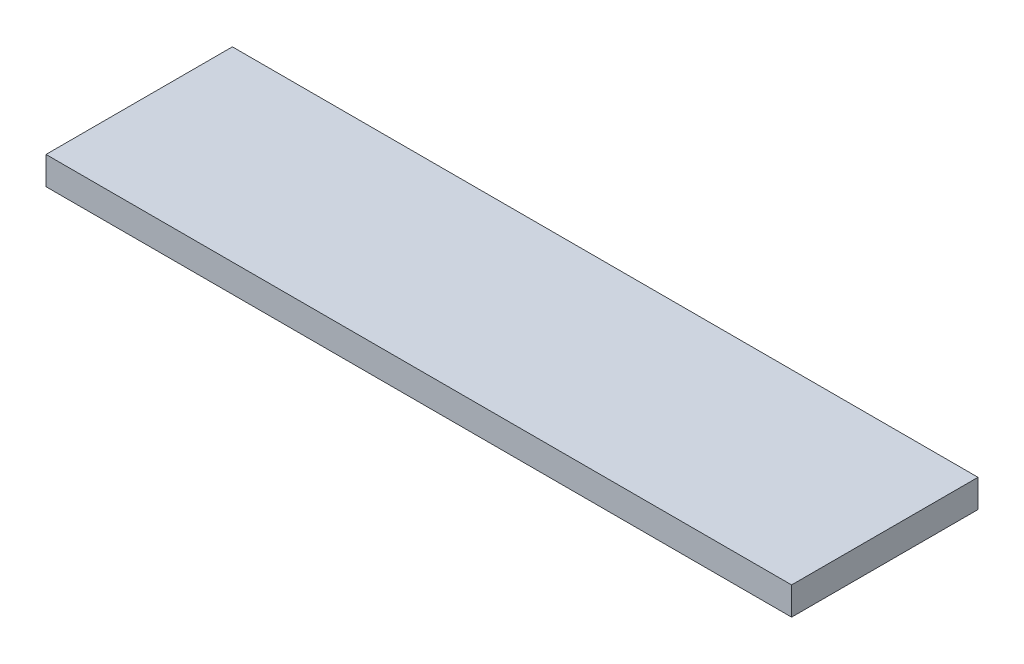
SolidWorks part; units mm, degrees
ref_plane "Front" through (0, 0, 0) normal (0, 0, 1) x (1, 0, 0)
ref_plane "Top" through (0, 0, 0) normal (0, 1, 0) x (1, 0, 0)
ref_plane "Right" through (0, 0, 0) normal (1, 0, 0) x (0, 0, -1)
sketch "Sketch1" plane through (0, 0, 0) normal (0, 1, 0) x (1, 0, 0)
  line L1 (-24.8447, 10.7453) -> (55.1553, 10.7453)
  line L2 (-24.8447, 10.7453) -> (-24.8447, -9.2547)
  line L3 (-24.8447, -9.2547) -> (55.1553, -9.2547)
  line L4 (55.1553, 10.7453) -> (55.1553, -9.2547)
  dimension "D1" = 20
  dimension "D2" = 80
extrude "Boss-Extrude1" add sketch "Sketch1" along normal blind 3
